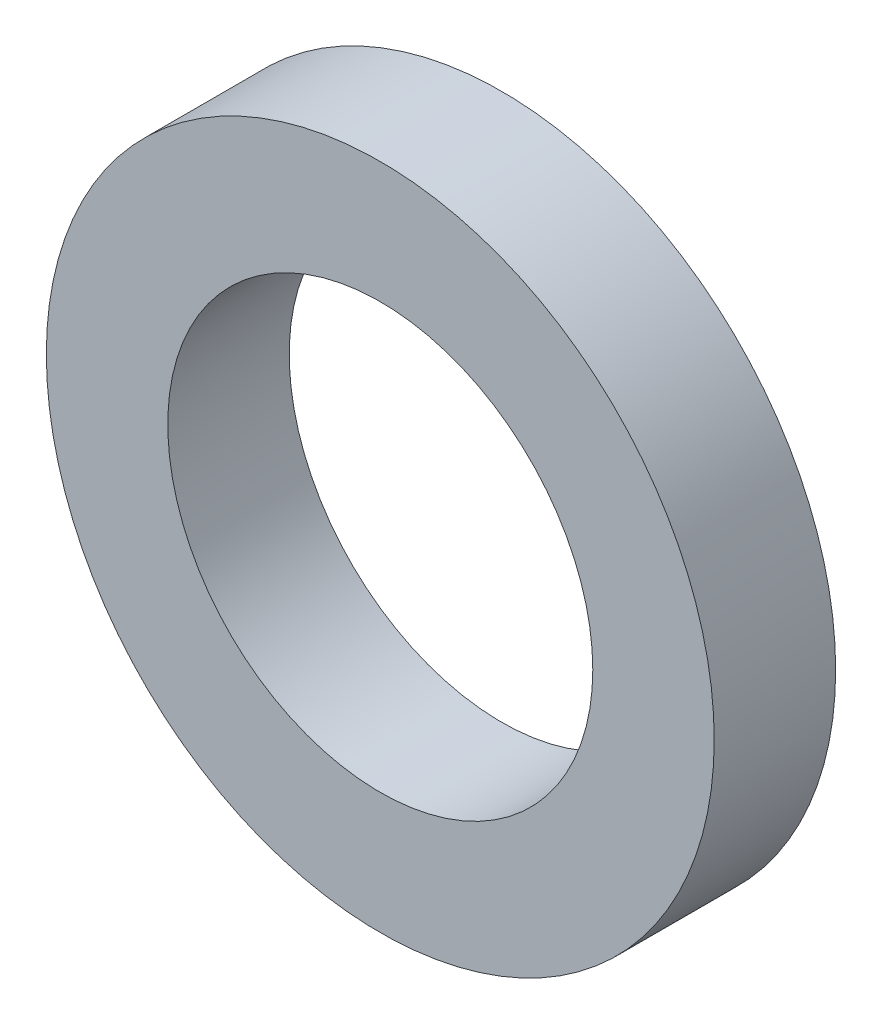
SolidWorks part; units mm, degrees
material "Laiton"
ref_plane "Plan de face" through (0, 0, 0) normal (0, 0, 1) x (1, 0, 0)
ref_plane "Plan de dessus" through (0, 0, 0) normal (0, 1, 0) x (1, 0, 0)
ref_plane "Plan de droite" through (0, 0, 0) normal (1, 0, 0) x (0, 0, -1)
sketch "Esquisse1" plane through (0, 0, 0) normal (0, 0, 1) x (1, 0, 0)
  circle A0 centre (0, 0) radius 3.5
  circle A1 centre (0, 0) radius 5.5
  dimension "D1" = 11
  dimension "D2" = 7
extrude "Boss.-Extru.1" add sketch "Esquisse1" along normal blind 2
